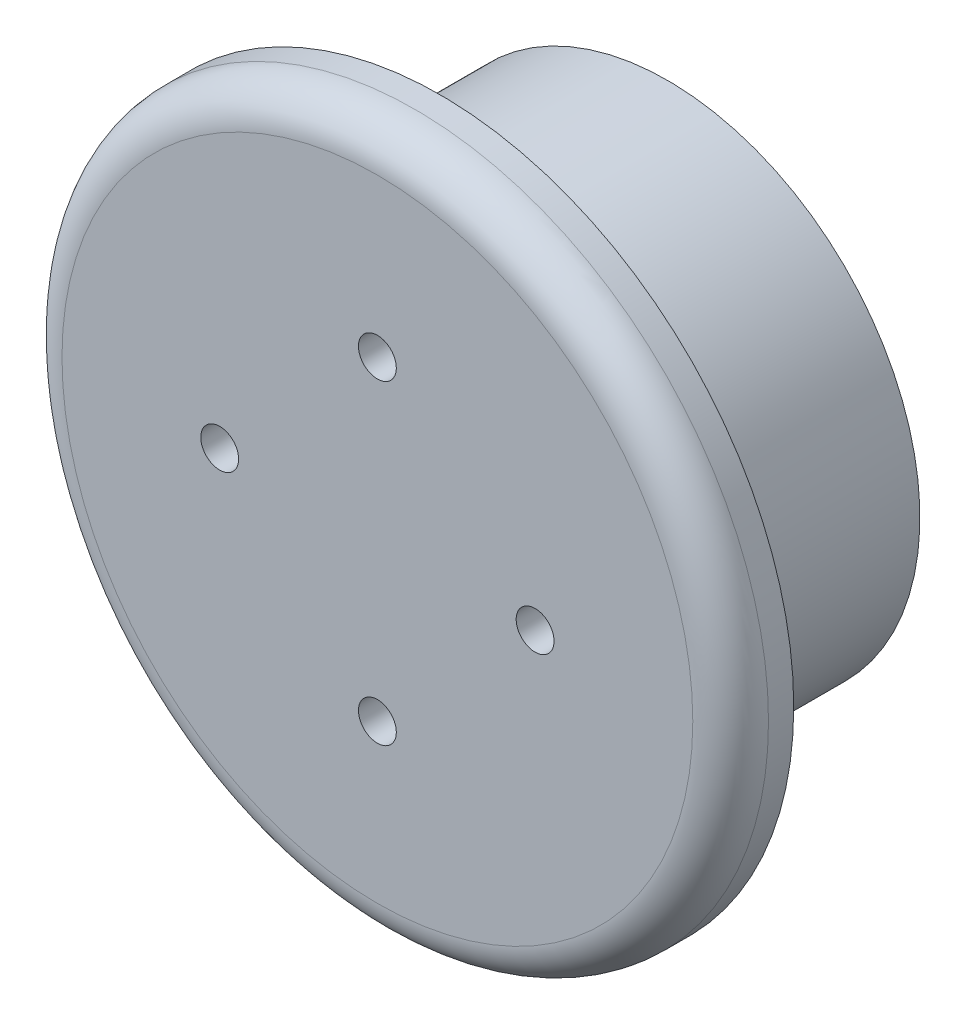
SolidWorks part; units mm, degrees
ref_plane "Front Plane" through (0, 0, 0) normal (1, 0, 0) x (0, 1, 0)
ref_plane "Top Plane" through (0, 0, 0) normal (0, 0, 1) x (0, 1, 0)
ref_plane "Right Plane" through (0, 0, 0) normal (0, 1, 0) x (-1, 0, 0)
sketch "Sketch1" plane through (0, 0, 0) normal (0, 0, 1) x (0, 1, 0)
  circle A0 centre (0, 0) radius 28
  dimension "D1" = 56
extrude "Boss-Extrude1" add sketch "Sketch1" along normal blind 5
fillet "Fillet1" radius 3 1 edges at (28, 0, 5)
sketch "Sketch2" plane through (0, 0, 0) normal (1, 0, 0) x (0, 1, 0)
  line L0 (0, 0) -> (0, 11.9501) construction
  line L1 (-19.075, 0) -> (-19.075, -2)
  line L2 (-28, 0) -> (28, 0) construction
  line L3 (-19.075, -2) -> (-20, -2)
  line L4 (-20, -2) -> (-20, -18)
  line L5 (-20, -18) -> (-17.5, -18)
  line L6 (-17.5, -18) -> (-17.5, -8)
  line L7 (-17.5, -8) -> (-12, -8)
  line L8 (-12, -8) -> (-12, -2)
  line L9 (-12, -2) -> (0, -2)
  line L10 (0, -2) -> (0, 0)
  line L11 (-19.075, 0) -> (0, 0)
  point P13 (0, 5.975)
  dimension "D1" = 38.15
  dimension "D2" = 20
  dimension "D3" = 16
  dimension "D4" = 10
  dimension "D5" = 18
  dimension "D6" = 17.5
  dimension "D7" = 12
revolve "Revolve1" add sketch "Sketch2" angle 360 about L0
chamfer "Chamfer1" distance 1 angle 45 1 edges at (-17.5, 0, -18)
sketch "Sketch3" plane through (0, 0, 5) normal (0, 0, 1) x (1, 0, 0)
  circle A0 centre (0, 0) radius 12.5 construction
  point P3 (0, 12.5)
  point P4 (-12.5, 0)
  point P5 (0, -12.5)
  point P6 (12.5, 0)
  point P7 (-12.5, 0)
  point P8 (0, 12.5)
  dimension "D1" = 25
hole_wizard "Tap Drill for M3 Tap1" positions "Sketch3" profile "Sketch4" hole size "M3" standard "ISO"
sketch "Sketch4" plane through (0, 12.5, 5) normal (1, 0, 0) x (0, -1, 0)
  line L0 (0, 0) -> (0, 4)
  line L1 (0, 4) -> (1.5, 3.0987)
  line L2 (1.5, 3.0987) -> (1.5, 0)
  line L5 (1.5, 0) -> (0, 0)
  line L10 (0, 4) -> (-1.5, 3.0987) construction
  line L11 (0, -6.35) -> (0, 107.95) construction
  dimension "Hole Dia." = 3
  dimension "Hole Depth" = 4
  dimension "Drill Angle" = 118
